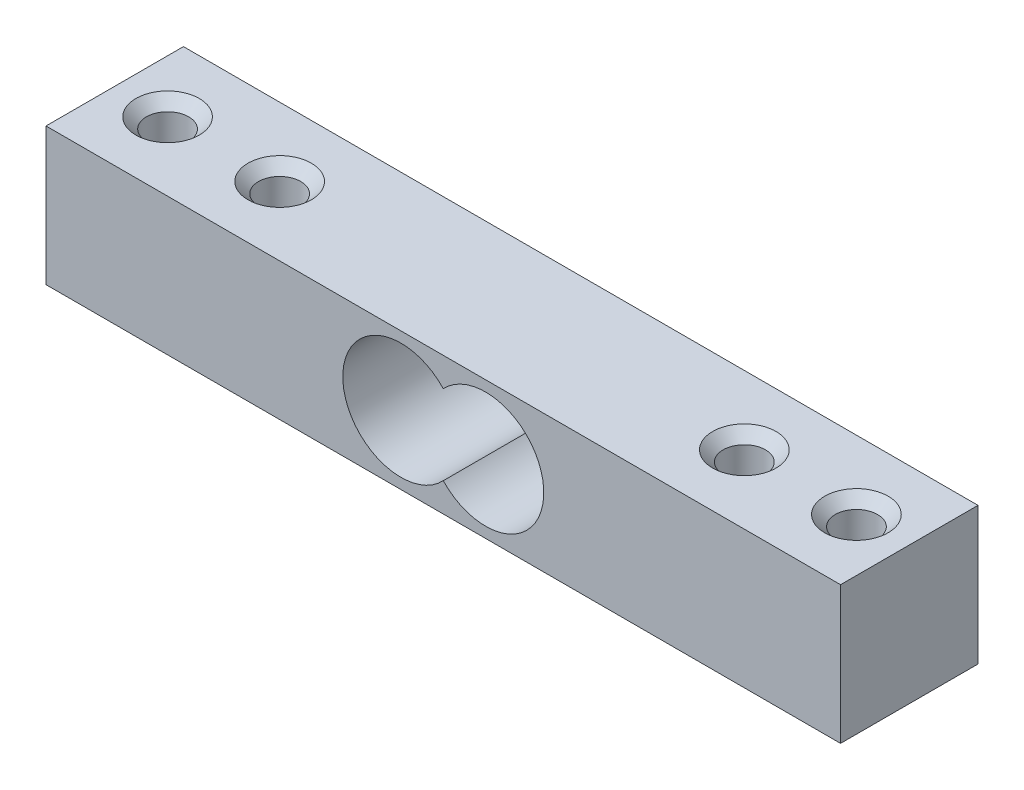
SolidWorks part; units mm, degrees
ref_plane "Front Plane" through (0, 0, 0) normal (0, 0, 1) x (1, 0, 0)
ref_plane "Top Plane" through (0, 0, 0) normal (0, 1, 0) x (1, 0, 0)
ref_plane "Right Plane" through (0, 0, 0) normal (1, 0, 0) x (0, 0, -1)
sketch "Sketch1" plane through (0, 0, 0) normal (0, 1, 0) x (1, 0, 0)
  line L1 (-40.1706, 13.7416) -> (34.9794, 13.7416)
  line L2 (-40.1706, 13.7416) -> (-40.1706, 0.7416)
  line L3 (-40.1706, 0.7416) -> (34.9794, 0.7416)
  line L4 (34.9794, 13.7416) -> (34.9794, 0.7416)
  circle A0 centre (29.9794, 7.2416) radius 2
  circle A1 centre (19.3794, 7.2416) radius 2
  circle A2 centre (-35.1706, 7.2416) radius 2
  circle A3 centre (-24.5706, 7.2416) radius 2
  dimension "D4" = 4
  dimension "D6" = 4
  dimension "D11" = 4
  dimension "D12" = 4
  dimension "D1" = 75.15
  dimension "D2" = 13
  dimension "D3" = 5
  dimension "D5" = 15.6
  dimension "D7" = 6.5
  dimension "D8" = 6.5
  dimension "D9" = 5
  dimension "D10" = 15.6
extrude "Boss-Extrude1" add sketch "Sketch1" along normal blind 13
chamfer "Chamfer1" distance 1 angle 45 1 edges at (19.3794, 0, -5.2416)
chamfer "Chamfer2" distance 1 angle 45 7 edges at (19.3794, 13, -5.2416) (29.9794, 13, -5.2416) (-24.5706, 13, -5.2416) (-35.1706, 13, -5.2416) (-24.5706, 0, -5.2416) (-35.1706, 0, -5.2416) (29.9794, 0, -5.2416)
sketch "Sketch2" plane through (0, 0, -0.7416) normal (0, 0, 1) x (1, 0, 0)
  line L0 (-25.2051, 13) -> (-25.2051, 0)
  line L1 (-40.1706, 13) -> (34.9794, 13) construction
  line L2 (-40.1706, 0) -> (34.9794, 0) construction
  line L3 (-40.1706, 6.5) -> (34.9794, 6.5)
  line L5 (-40.1706, 13) -> (-40.1706, 0) construction
  line L6 (34.9794, 13) -> (34.9794, 0) construction
  circle A0 centre (1.4094, 6.5) radius 5.5
  circle A1 centre (-6.6006, 6.5) radius 5.5
  dimension "D3" = 11
  dimension "D4" = 11
  dimension "D1" = 0
  dimension "D2" = 41.58
  dimension "D5" = 41.58
extrude "Cut-Extrude1" cut sketch "Sketch2" against normal blind 13 contours A0 A1 L3 | L3 A1 A0 | L3 A1 A0 | A1 L3 A0 | A1 A0 L3 | A0 A1 L3
